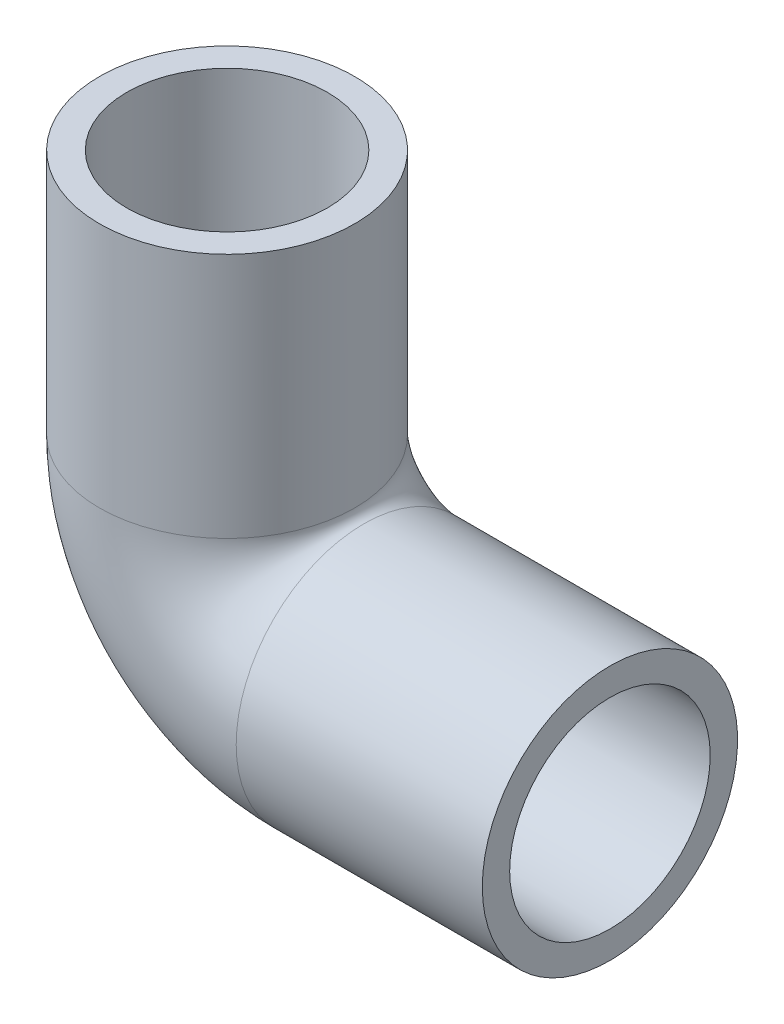
SolidWorks part; units mm, degrees
material "PVC 0.007 Plasticized"
ref_plane "Front Plane" through (0, 0, 0) normal (0, 0, 1) x (1, 0, 0)
ref_plane "Top Plane" through (0, 0, 0) normal (0, 1, 0) x (1, 0, 0)
ref_plane "Right Plane" through (0, 0, 0) normal (1, 0, 0) x (0, 0, -1)
sketch "Sketch1" plane through (0, 0, 0) normal (0, 0, 1) x (1, 0, 0)
  line L0 (0, 42) -> (0, 15)
  line L1 (42, 0) -> (15, 0)
  arc A0 (0, 15) -> (15, 0) centre (15, 15) ccw
  point P3 (20, 0)
  point P5 (0, 20)
  point P8 (0, 0)
  point P9 (0, 0)
  point P10 (0, 42)
  point P11 (42, 0)
  point P13 (0, 0)
  dimension "D1" = 15
  dimension "D6" = 42
  dimension "D7" = 42
ref_plane "Plane1" through (0, 42, 0) normal (0, 1, 0) x (1, 0, 0)
sketch "Sketch2" plane through (0, 42, 0) normal (0, 1, 0) x (1, 0, 0)
  circle A0 centre (0, 0) radius 14
  circle A1 centre (0, 0) radius 11
sweep "Sweep2" add profiles "Sketch2" path "Sketch1"
